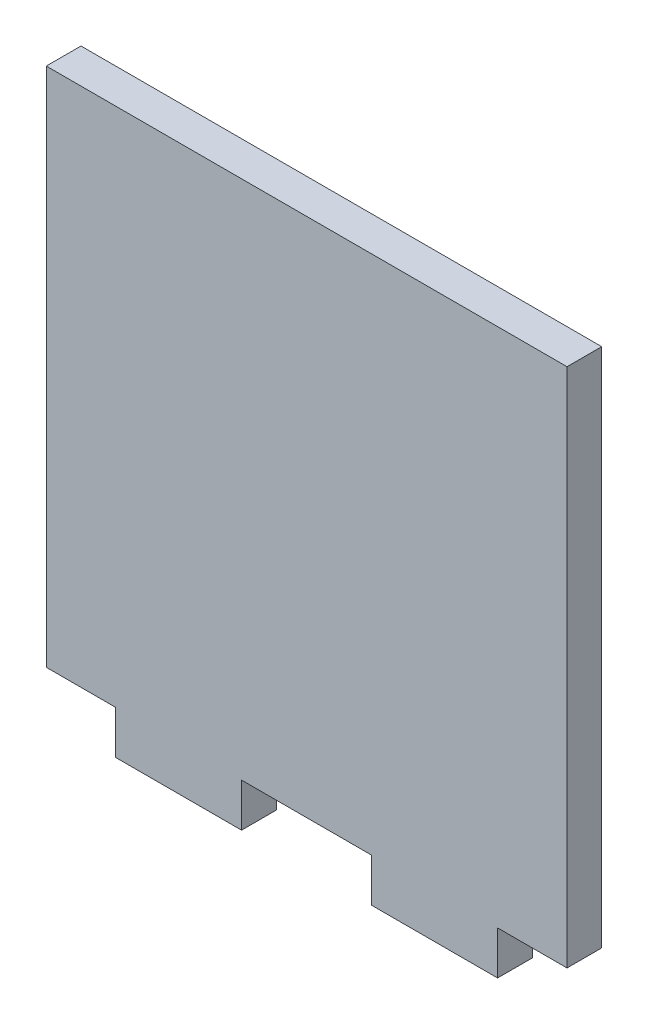
SolidWorks part; units mm, degrees
ref_plane "Front Plane" through (0, 0, 0) normal (0, 0, 1) x (1, 0, 0)
ref_plane "Top Plane" through (0, 0, 0) normal (0, 1, 0) x (1, 0, 0)
ref_plane "Right Plane" through (0, 0, 0) normal (1, 0, 0) x (0, 0, -1)
sketch "Sketch1" plane through (0, 0, 0) normal (0, 1, 0) x (1, 0, 0)
  line L1 (-30, -2) -> (30, -2)
  line L2 (-30, -2) -> (-30, 2)
  line L3 (-30, 2) -> (30, 2)
  line L4 (30, -2) -> (30, 2)
  line L5 (-30, -2) -> (30, 2) construction
  line L6 (-30, 2) -> (30, -2) construction
  point P0 (0, 0)
  dimension "D1" = 60
  dimension "D2" = 4
extrude "Boss-Extrude1" add sketch "Sketch1" along normal blind 60
sketch "Sketch2" plane through (0, 0, 0) normal (0, -1, 0) x (-1, 0, 0)
  line L18 (22, -2) -> (22, 2)
  line L19 (30, -2) -> (-30, -2) construction
  line L20 (-30, 2) -> (30, 2) construction
  line L21 (22, 2) -> (7.5, 2)
  line L22 (7.5, 2) -> (7.5, -2)
  line L23 (7.5, -2) -> (22, -2)
  line L28 (0, 2.2) -> (0, -2.2) construction
  line L29 (-7.5, 2) -> (-7.5, -2)
  line L30 (-22, 2) -> (-7.5, 2)
  line L31 (-22, -2) -> (-22, 2)
  line L32 (-7.5, -2) -> (-22, -2)
  point P14 (-7.5, 0)
  dimension "D1" = 15
  dimension "D2" = 14.5
extrude "Boss-Extrude2" add sketch "Sketch2" along normal blind 5
